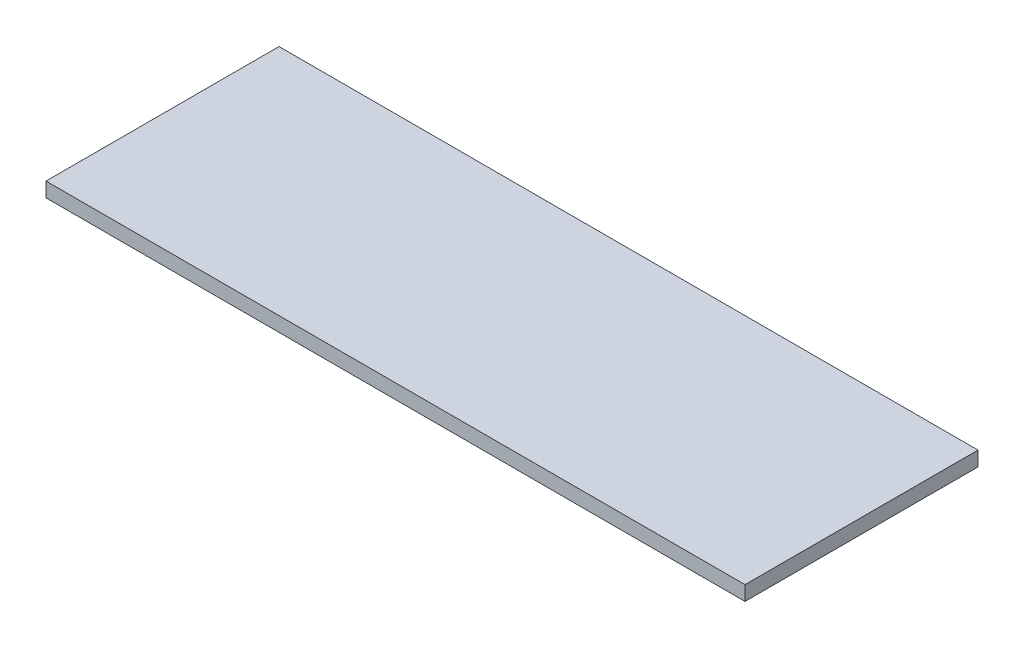
SolidWorks part; units mm, degrees
ref_plane "Front Plane" through (0, 0, 0) normal (0, 0, 1) x (1, 0, 0)
ref_plane "Top Plane" through (0, 0, 0) normal (0, 1, 0) x (1, 0, 0)
ref_plane "Right Plane" through (0, 0, 0) normal (1, 0, 0) x (0, 0, -1)
sketch "Sketch1" plane through (0, 0, 0) normal (0, 1, 0) x (1, 0, 0)
  line L1 (304.8, -101.6) -> (-304.8, -101.6)
  line L2 (304.8, -101.6) -> (304.8, 101.6)
  line L3 (304.8, 101.6) -> (-304.8, 101.6)
  line L4 (-304.8, -101.6) -> (-304.8, 101.6)
  line L5 (0, 101.6) -> (0, -101.6) construction
  line L6 (304.8, 0) -> (-304.8, 0) construction
  point P0 (0, 0)
  dimension "D1" = 203.2
  dimension "D2" = 609.6
extrude "Boss-Extrude1" add sketch "Sketch1" along normal blind 12.7
sketch "Sketch2" plane through (0, 12.7, 0) normal (0, 1, 0) x (1, 0, 0)
  line L0 (0, 76.2) -> (0, 101.6) construction
  line L1 (-221.4099, 76.2) -> (221.4099, 76.2)
  line L2 (-226.9979, 70.612) -> (-226.9979, 19.812)
  line L3 (-221.4099, 14.224) -> (221.4099, 14.224)
  line L4 (226.9979, 70.612) -> (226.9979, 19.812)
  line L5 (0, 14.224) -> (0, 76.2) construction
  line L6 (-226.9979, 45.212) -> (226.9979, 45.212) construction
  line L7 (304.8, 101.6) -> (-304.8, 101.6) construction
  line L8 (-221.4099, -19.05) -> (-61.1651, -19.05)
  line L9 (-226.9979, -24.638) -> (-226.9979, -75.438)
  line L10 (-221.4099, -81.026) -> (-61.1651, -81.026)
  line L11 (-55.5771, -24.638) -> (-55.5771, -75.438)
  line L12 (-141.2875, -81.026) -> (-141.2875, -19.05) construction
  line L13 (-226.9979, -50.038) -> (-55.5771, -50.038) construction
  line L14 (-226.9979, 19.812) -> (-226.9979, -24.638) construction
  arc A1 (221.4099, 76.2) -> (226.9979, 70.612) centre (221.4099, 70.612) cw
  arc A2 (221.4099, 14.224) -> (226.9979, 19.812) centre (221.4099, 19.812) ccw
  arc A3 (-226.9979, 19.812) -> (-221.4099, 14.224) centre (-221.4099, 19.812) ccw
  arc A4 (-221.4099, 76.2) -> (-226.9979, 70.612) centre (-221.4099, 70.612) ccw
  arc A5 (-61.1651, -19.05) -> (-55.5771, -24.638) centre (-61.1651, -24.638) cw
  arc A6 (-61.1651, -81.026) -> (-55.5771, -75.438) centre (-61.1651, -75.438) ccw
  arc A7 (-226.9979, -75.438) -> (-221.4099, -81.026) centre (-221.4099, -75.438) ccw
  arc A8 (-221.4099, -19.05) -> (-226.9979, -24.638) centre (-221.4099, -24.638) ccw
  point P0 (0, 45.212)
  point P17 (-141.2875, -50.038)
  dimension "D1" = 5.588
  dimension "D2" = 1022.35
  dimension "D6" = 5.588
  dimension "D7" = 457.2
  dimension "D3" = 25.4
  dimension "D4" = 50.8
  dimension "D5" = 50.8
  dimension "D8" = 44.45
